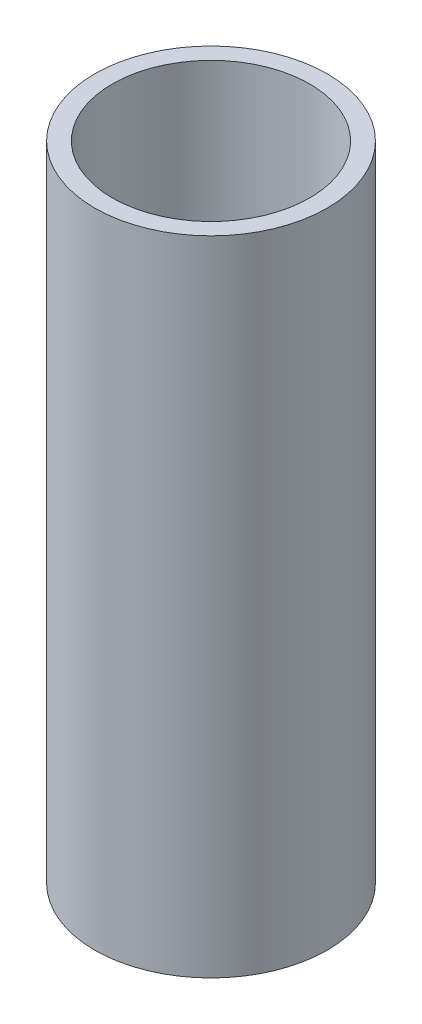
SolidWorks part; units mm, degrees
ref_plane "Front Plane" through (0, 0, 0) normal (0, 0, 1) x (1, 0, 0)
ref_plane "Top Plane" through (0, 0, 0) normal (0, 1, 0) x (1, 0, 0)
ref_plane "Right Plane" through (0, 0, 0) normal (1, 0, 0) x (0, 0, -1)
sketch "Sketch1" plane through (0, 0, 0) normal (0, 1, 0) x (1, 0, 0)
  circle A0 centre (0, 0) radius 19.9
  dimension "D1" = 39.8
extrude "Boss-Extrude1" add sketch "Sketch1" along normal mid plane 110
sketch "Sketch2" plane through (0, 55, 0) normal (0, 1, 0) x (1, 0, 0)
  circle A0 centre (0, 0) radius 16.9
  circle A1 centre (0, 0) radius 19.9 construction
  dimension "D1" = 3
extrude "Cut-Extrude1" cut sketch "Sketch2" against normal blind 123
